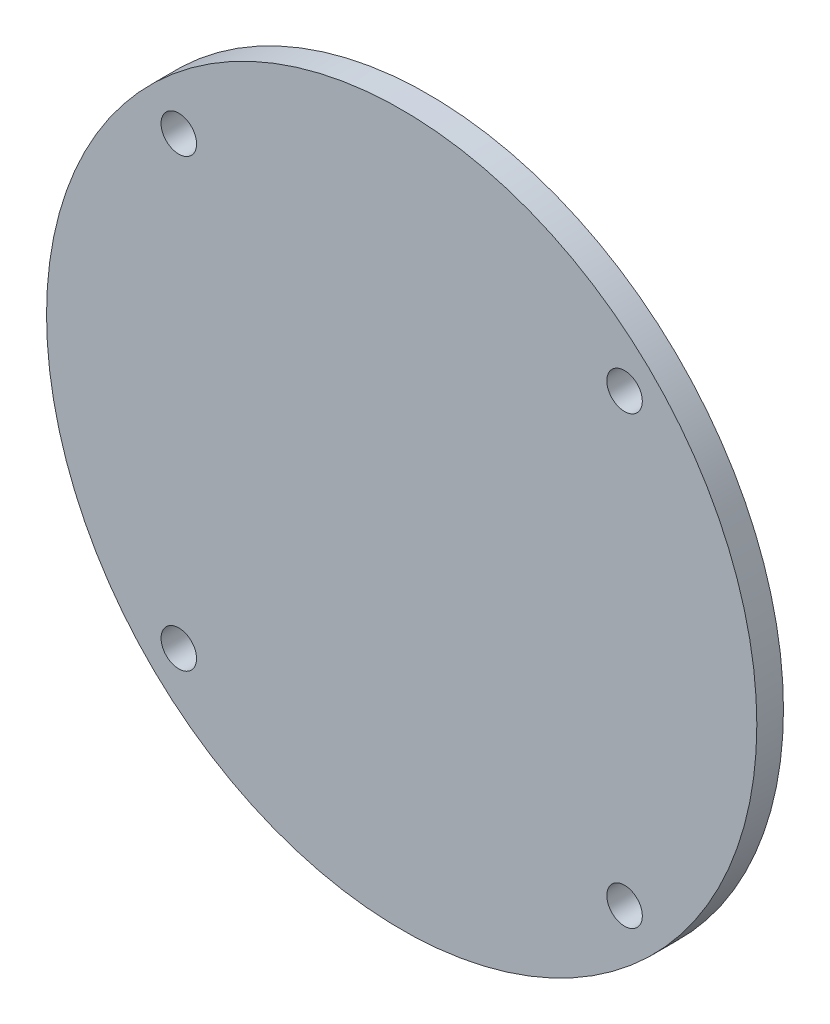
SolidWorks part; units mm, degrees
ref_plane "前视基准面" through (0, 0, 0) normal (0, 0, 1) x (1, 0, 0)
ref_plane "上视基准面" through (0, 0, 0) normal (0, 1, 0) x (1, 0, 0)
ref_plane "右视基准面" through (0, 0, 0) normal (1, 0, 0) x (0, 0, -1)
sketch "草图1" plane through (0, 0, 0) normal (0, 0, 1) x (1, 0, 0)
  line L1 (-25.1023, -25.1023) -> (25.1023, -25.1023)
  line L2 (-25.1023, -25.1023) -> (-25.1023, 25.1023)
  line L3 (-25.1023, 25.1023) -> (25.1023, 25.1023)
  line L4 (25.1023, -25.1023) -> (25.1023, 25.1023)
  line L5 (-25.1023, -25.1023) -> (25.1023, 25.1023) construction
  line L6 (-25.1023, 25.1023) -> (25.1023, -25.1023) construction
  circle A0 centre (0, 0) radius 40
  circle A1 centre (-25.1023, 25.1023) radius 2
  circle A2 centre (25.1023, 25.1023) radius 2
  circle A3 centre (25.1023, -25.1023) radius 2
  circle A4 centre (-25.1023, -25.1023) radius 2
  dimension "D2" = 80
  dimension "D4" = 4
  dimension "D5" = 4
  dimension "D6" = 4
  dimension "D7" = 4
  dimension "D1" = 71
extrude "凸台-拉伸1" add sketch "草图1" along normal blind 3 contours A0 A4 L2 A1 L3 A2 L4 A3 L1 | A4 L1 A3 L4 A2 L3 A1 L2
